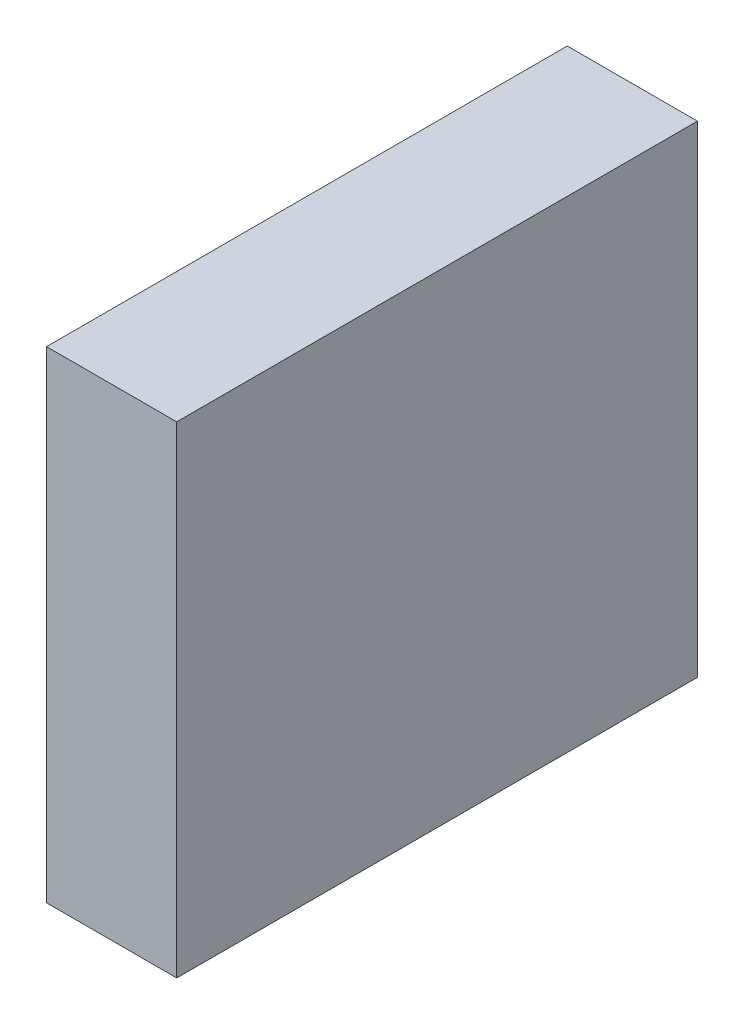
SolidWorks part; units mm, degrees
ref_plane "Front Plane" through (0, 0, 0) normal (0, 0, 1) x (1, 0, 0)
ref_plane "Top Plane" through (0, 0, 0) normal (0, 1, 0) x (1, 0, 0)
ref_plane "Right Plane" through (0, 0, 0) normal (1, 0, 0) x (0, 0, -1)
sketch "Sketch1" plane through (0, 0, 0) normal (1, 0, 0) x (0, 0, -1)
  line L1 (0, 0) -> (40, 0)
  line L2 (0, 0) -> (0, 37)
  line L3 (0, 37) -> (40, 37)
  line L4 (40, 0) -> (40, 37)
extrude "Boss-Extrude1" add sketch "Sketch1" along normal blind 10
